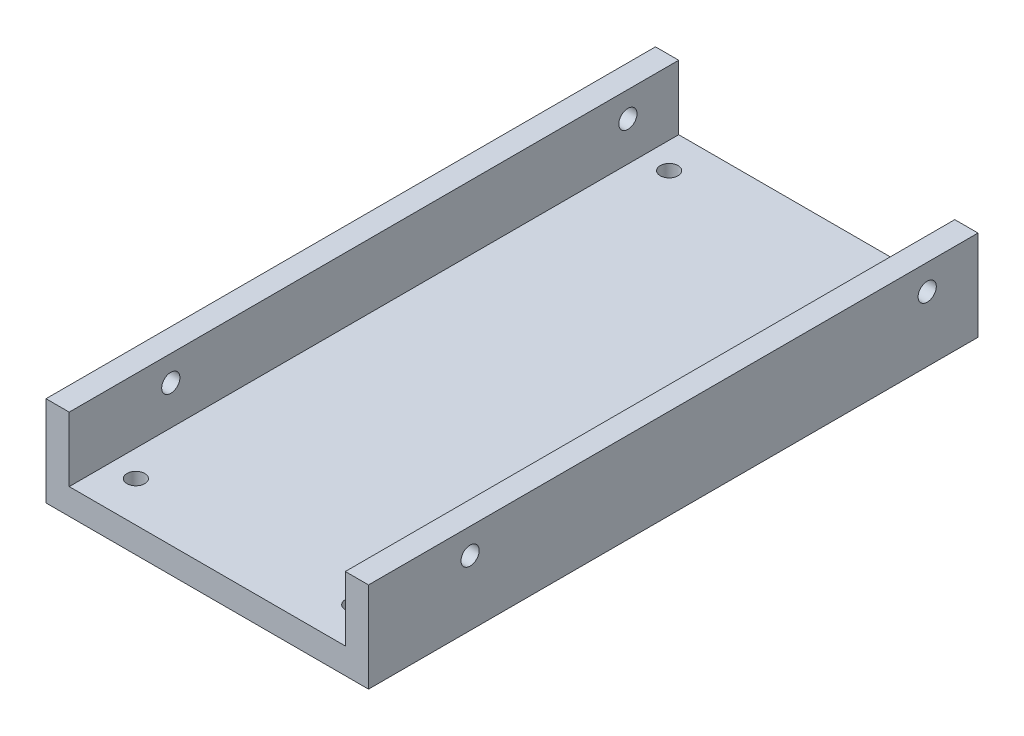
SolidWorks part; units mm, degrees
ref_plane "Front Plane" through (0, 0, 0) normal (0, 0, 1) x (1, 0, 0)
ref_plane "Top Plane" through (0, 0, 0) normal (0, 1, 0) x (1, 0, 0)
ref_plane "Right Plane" through (0, 0, 0) normal (1, 0, 0) x (0, 0, -1)
sketch "Sketch2" plane through (0, 0, 0) normal (0, 1, 0) x (1, 0, 0)
  line L1 (-53.222, 98.2514) -> (10.278, 98.2514)
  line L2 (-53.222, 98.2514) -> (-53.222, -21.7486)
  line L3 (-53.222, -21.7486) -> (10.278, -21.7486)
  line L4 (10.278, 98.2514) -> (10.278, -21.7486)
  dimension "D1" = 63.5
  dimension "D2" = 120
extrude "Boss-Extrude1" add sketch "Sketch2" along normal blind 5.08
sketch "Sketch3" plane through (0, 5.08, 0) normal (0, 1, 0) x (1, 0, 0)
  line L0 (10.278, 98.2514) -> (-53.222, 98.2514) construction
  line L1 (-53.222, -21.7486) -> (-48.65, -21.7486)
  line L2 (-53.222, -21.7486) -> (-53.222, 98.2514)
  line L3 (-53.222, 98.2514) -> (-48.65, 98.2514)
  line L4 (-48.65, -21.7486) -> (-48.65, 98.2514)
  line L6 (10.278, -21.7486) -> (5.706, -21.7486)
  line L7 (10.278, -21.7486) -> (10.278, 98.2514)
  line L8 (10.278, 98.2514) -> (5.706, 98.2514)
  line L9 (5.706, -21.7486) -> (5.706, 98.2514)
  dimension "D1" = 4.572
extrude "Boss-Extrude2" add sketch "Sketch3" along normal blind 12.7
sketch "Sketch4" plane through (10.278, 0, 0) normal (1, 0, 0) x (0, 0, -1)
  line L0 (-21.7486, 17.78) -> (98.2514, 17.78) construction
  line L2 (98.2514, 17.78) -> (98.2514, 0) construction
  circle A0 centre (-1.7486, 12.78) radius 1.791
  circle A1 centre (88.2514, 12.78) radius 1.791
  dimension "D1" = 5
  dimension "D2" = 90
  dimension "D3" = 10
extrude "Cut-Extrude1" cut sketch "Sketch4" against normal up to surface (63.5 mm away) up to face at (-53.222, 8.89, -38.2514)
sketch "Sketch5" plane through (0, 0, 0) normal (0, -1, 0) x (-1, 0, 0)
  line L0 (0.4564, -13.8207) -> (0.4564, 91.1793) construction
  line L1 (0.4564, 91.1793) -> (43.4564, 91.1793) construction
  line L2 (43.4564, 91.1793) -> (43.4564, -13.8207) construction
  line L3 (43.4564, -13.8207) -> (0.4564, -13.8207) construction
  circle A0 centre (43.4564, 91.1793) radius 1.75
  circle A1 centre (0.4564, 91.1793) radius 1.75
  circle A2 centre (43.4564, -13.8207) radius 1.75
  circle A3 centre (0.4564, -13.8207) radius 1.75
  dimension "D3" = 3.5
  dimension "D1" = 43
  dimension "D2" = 105
extrude "Cut-Extrude2" cut sketch "Sketch5" against normal through all
